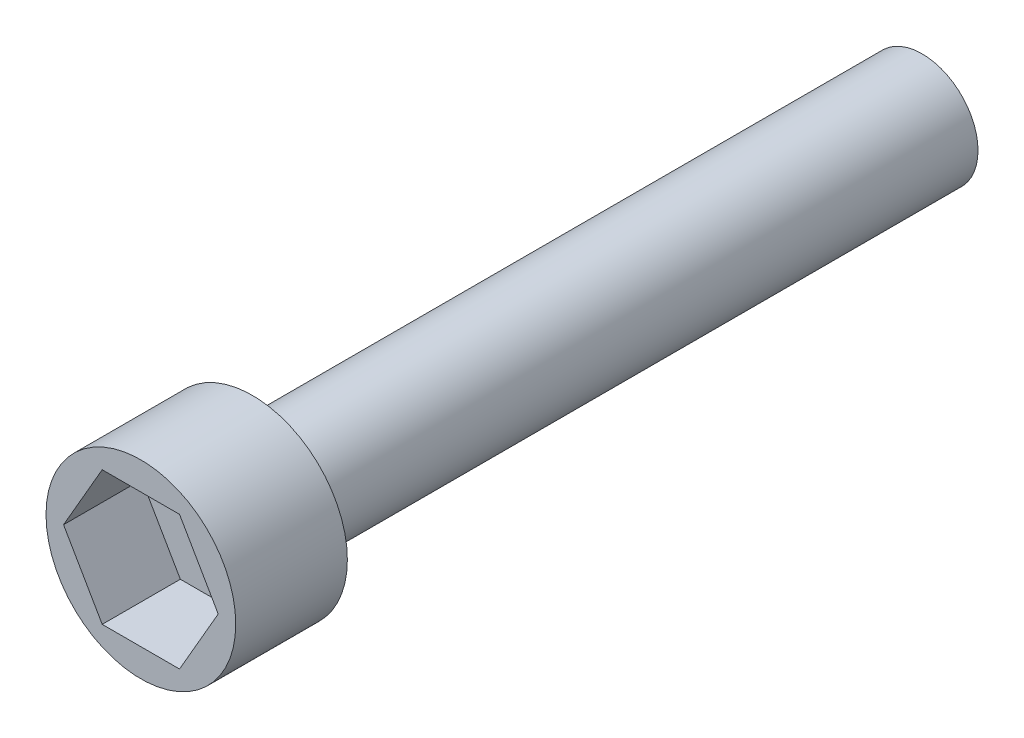
SolidWorks part; units mm, degrees
ref_plane "Plan de face" through (0, 0, 0) normal (0, 0, 1) x (1, 0, 0)
ref_plane "Plan de dessus" through (0, 0, 0) normal (0, 1, 0) x (1, 0, 0)
ref_plane "Plan de droite" through (0, 0, 0) normal (1, 0, 0) x (0, 0, -1)
sketch "Esquisse1" plane through (0, 0, 0) normal (0, 0, 1) x (1, 0, 0)
  circle A0 centre (0, 0) radius 2.5
  dimension "D1" = 5
extrude "Boss.-Extru.1" add sketch "Esquisse1" along normal blind 30
sketch "Esquisse2" plane through (0, 0, 30) normal (0, 0, 1) x (1, 0, 0)
  circle A0 centre (0, 0) radius 4.25
  dimension "D1" = 8.5
extrude "Boss.-Extru.2" add sketch "Esquisse2" along normal blind 5
sketch "Esquisse3" plane through (0, 0, 35) normal (0, 0, 1) x (1, 0, 0)
  line L1 (3.4641, 0) -> (1.7321, 3)
  line L2 (1.7321, 3) -> (-1.7321, 3)
  line L3 (-1.7321, 3) -> (-3.4641, 0)
  line L4 (-3.4641, 0) -> (-1.7321, -3)
  line L5 (-1.7321, -3) -> (1.7321, -3)
  line L6 (1.7321, -3) -> (3.4641, 0)
  circle A0 centre (0, 0) radius 3 construction
  dimension "D1" = 6
extrude "Enlèv. mat.-Extru.1" cut sketch "Esquisse3" against normal blind 3.5
